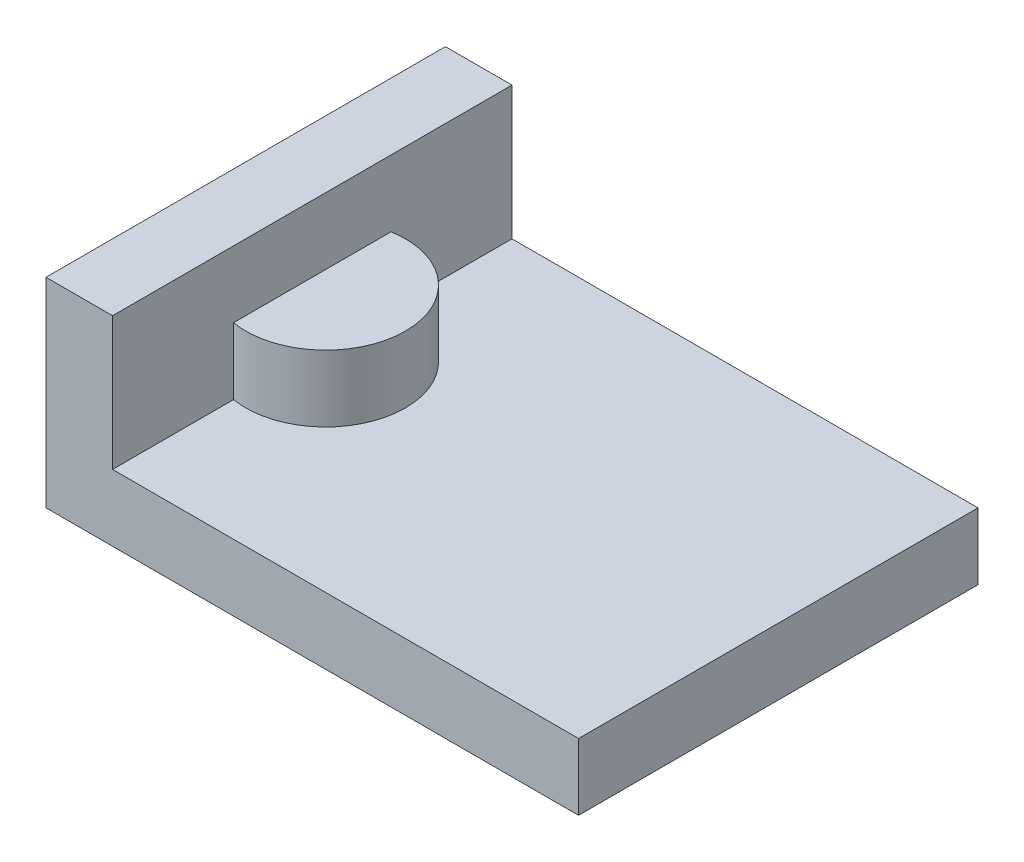
SolidWorks part; units mm, degrees
ref_plane "Front Plane" through (0, 0, 0) normal (0, 0, 1) x (1, 0, 0)
ref_plane "Top Plane" through (0, 0, 0) normal (0, 1, 0) x (1, 0, 0)
ref_plane "Right Plane" through (0, 0, 0) normal (1, 0, 0) x (0, 0, -1)
sketch "Sketch1" plane through (0, 0, 0) normal (0, 1, 0) x (1, 0, 0)
  line L1 (-40, -30) -> (40, -30)
  line L2 (-40, -30) -> (-40, 30)
  line L3 (-40, 30) -> (40, 30)
  line L4 (40, -30) -> (40, 30)
extrude "Boss-Extrude1" add sketch "Sketch1" along normal blind 10
sketch "Sketch2" plane through (0, 0, 0) normal (0, 1, 0) x (1, 0, 0)
  line L1 (-40, -30) -> (-30, -30)
  line L2 (-40, -30) -> (-40, 30)
  line L3 (-40, 30) -> (-30, 30)
  line L4 (-30, -30) -> (-30, 30)
extrude "Boss-Extrude2" add sketch "Sketch2" along normal blind 30
sketch "Sketch3" plane through (0, 0, 0) normal (0, 1, 0) x (1, 0, 0)
  circle A0 centre (-28, 0) radius 12
extrude "Boss-Extrude3" add sketch "Sketch3" along normal blind 20
